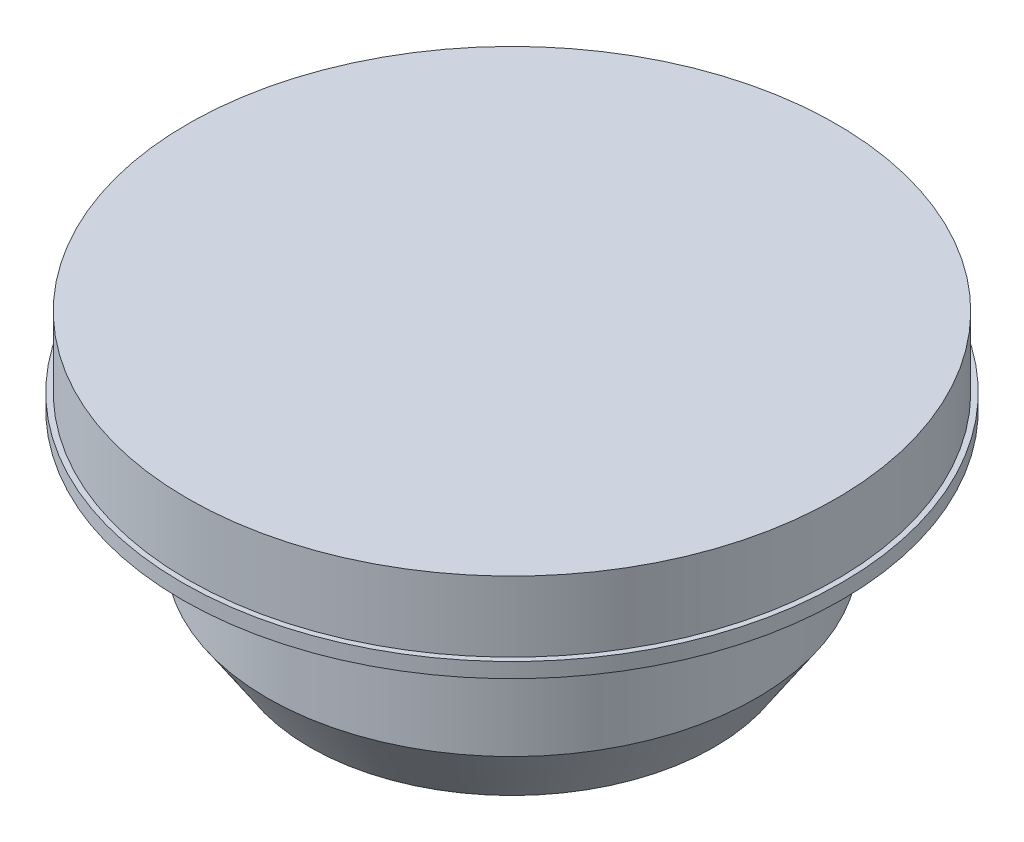
SolidWorks part; units mm, degrees
ref_plane "Front Plane" through (0, 0, 0) normal (0, 0, 1) x (1, 0, 0)
ref_plane "Top Plane" through (0, 0, 0) normal (0, 1, 0) x (1, 0, 0)
ref_plane "Right Plane" through (0, 0, 0) normal (1, 0, 0) x (0, 0, -1)
sketch "Sketch1" plane through (0, 0, 0) normal (0, 1, 0) x (1, 0, 0)
  circle A0 centre (0, 0) radius 1.525
  dimension "D1" = 3.05
extrude "Boss-Extrude1" add sketch "Sketch1" along normal blind 0.4
sketch "Sketch3" plane through (0, 0.4, 0) normal (0, 1, 0) x (1, 0, 0)
  circle A0 centre (0, 0) radius 1.55
  dimension "D1" = 3.1
extrude "Boss-Extrude2" add sketch "Sketch3" against normal blind 0.07 from offset 0.33 offset against normal yes
sketch "Sketch4" plane through (0, 0, 0) normal (0, -1, 0) x (1, 0, 0)
  circle A0 centre (0, 0) radius 1.15
  dimension "D1" = 2.3
extrude "Boss-Extrude3" add sketch "Sketch4" along normal blind 0.9
sketch "Sketch5" plane through (0, 0, 0) normal (0, 0, 1) x (1, 0, 0)
  line L0 (-1.15, -0.6) -> (-0.95, -0.9)
  line L1 (-1.15, 0) -> (-1.15, -0.9) construction
  line L2 (-1.15, -0.9) -> (1.15, -0.9) construction
  line L3 (-0.95, -0.9) -> (-1.15, -0.9)
  line L4 (-1.15, -0.9) -> (-1.15, -0.6)
  dimension "D1" = 0.3
  dimension "D2" = 0.2
sketch "Sketch6" plane through (0, -0.9, 0) normal (0, -1, 0) x (1, 0, 0)
  point P0 (0, 0)
ref_axis "Axis1" through (0, -0.9, 0) along (0, -1, 0)
revolve "Cut-Revolve1" cut sketch "Sketch5" angle 360 about axis through (0, -0.9, 0) along (0, -1, 0)
sketch "Sketch7" plane through (0, 0, 0) normal (0, 0, 1) x (1, 0, 0)
  line L0 (-1.15, -0.1) -> (-1.25, 0)
  line L1 (-1.15, 0) -> (-1.15, -0.6) construction
  line L2 (-1.55, 0) -> (1.55, 0) construction
  line L3 (-1.25, 0) -> (-1.15, 0)
  line L4 (-1.15, 0) -> (-1.15, -0.1)
  dimension "D1" = 0.1
  dimension "D2" = 0.1
revolve "Revolve1" add sketch "Sketch7" angle 360 about axis through (0, -0.9, 0) along (0, -1, 0)
